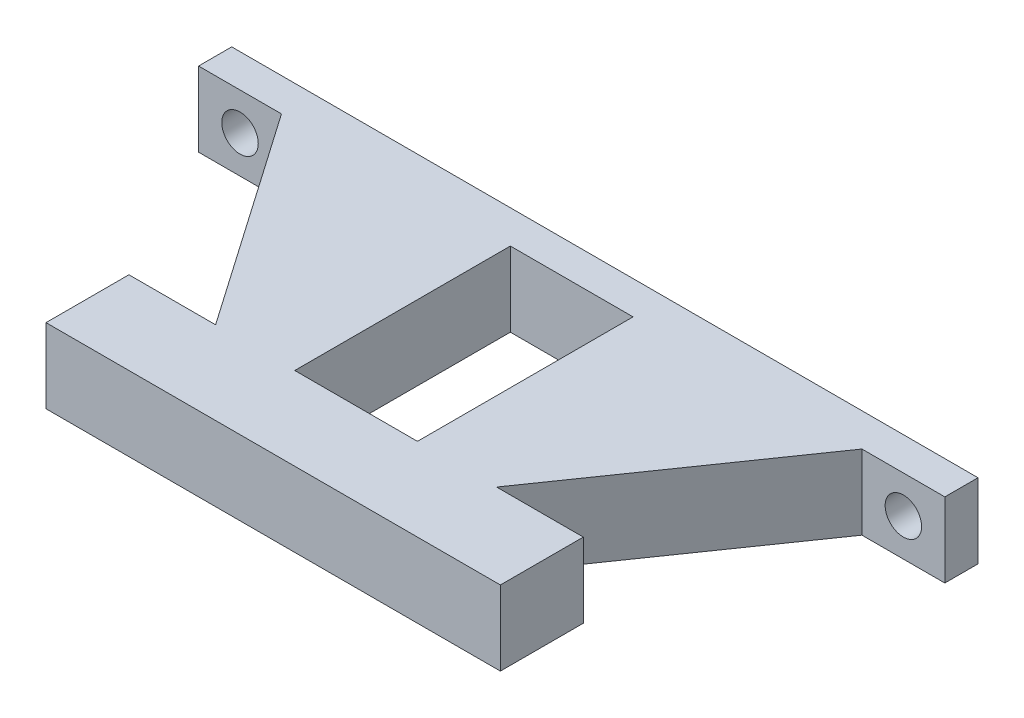
SolidWorks part; units mm, degrees
ref_plane "Front Plane" through (0, 0, 0) normal (0, 0, 1) x (1, 0, 0)
ref_plane "Top Plane" through (0, 0, 0) normal (0, 1, 0) x (1, 0, 0)
ref_plane "Right Plane" through (0, 0, 0) normal (1, 0, 0) x (0, 0, -1)
sketch "Sketch1" plane through (0, 0, 0) normal (0, 0, 1) x (1, 0, 0)
  line L3 (0, 2.54) -> (0, 16.409)
  line L4 (-57.15, 2.54) -> (-57.15, -2.54)
  line L6 (57.15, 2.54) -> (57.15, -2.54)
  line L9 (57.15, 2.54) -> (57.15, 5.715)
  line L10 (-57.15, 2.54) -> (-57.15, 5.715)
  line L11 (0, 0) -> (6.9271, 0)
  line L12 (57.15, -2.54) -> (57.15, -5.715)
  line L13 (-57.15, -2.54) -> (-57.15, -5.715)
  line L14 (-57.15, 5.715) -> (57.15, 5.715)
  line L15 (57.15, -5.715) -> (-57.15, -5.715)
  circle A0 centre (50.8, 0) radius 2.794
  circle A1 centre (-50.8, 0) radius 2.794
  point P4 (0, 0)
  dimension "D2" = 5.588
  dimension "D3" = 5.588
  dimension "D1" = 101.6
  dimension "D5" = 3.175
  dimension "D6" = 3.175
extrude "Boss-Extrude1" add sketch "Sketch1" along normal blind 5.08
sketch "Sketch2" plane through (0, 5.715, 0) normal (0, 1, 0) x (1, 0, 0)
  line L0 (-57.15, 0) -> (-57.15, -5.08)
  line L1 (-57.15, 0) -> (57.0574, 0)
  line L2 (-57.15, -5.08) -> (57.0574, -5.08)
  line L3 (57.0574, 0) -> (57.0574, -5.08)
sketch "Sketch3" plane through (0, 0, 5.08) normal (0, 0, 1) x (1, 0, 0)
  line L0 (-57.15, 5.715) -> (57.0574, 5.715) construction
  line L1 (-12.7, -5.715) -> (12.7, -5.715)
  line L2 (-12.7, -5.715) -> (-12.7, 5.715)
  line L3 (-12.7, 5.715) -> (12.7, 5.715)
  line L4 (12.7, -5.715) -> (12.7, 5.715)
  line L5 (-12.7, -5.715) -> (12.7, 5.715) construction
  line L6 (-12.7, 5.715) -> (12.7, -5.715) construction
  point P0 (0, 0)
  dimension "D1" = 25.4
extrude "Boss-Extrude2" add sketch "Sketch3" along normal blind 45.72
sketch "Sketch4" plane through (0, 0, 50.8) normal (0, 0, 1) x (1, 0, 0)
  line L0 (0, 0) -> (0, 10.3542)
  line L1 (-12.7, -5.715) -> (12.7, -5.715) construction
  line L2 (12.7, 5.715) -> (34.7967, 5.715)
  line L3 (12.7, 5.715) -> (12.7, -5.715)
  line L4 (12.7, -5.715) -> (34.7967, -5.715)
  line L5 (34.7967, 5.715) -> (34.7967, -5.715)
  line L6 (-12.7, -5.715) -> (-34.7967, -5.715)
  line L7 (-34.7967, 5.715) -> (-34.7967, -5.715)
  line L8 (-12.7, 5.715) -> (-34.7967, 5.715)
  line L9 (-12.7, 5.715) -> (-12.7, -5.715)
  line M6 (12.7, -5.715) -> (12.7, 5.715)
  line M8 (-12.7, 5.715) -> (-12.7, -5.715)
  dimension "D1" = 0
extrude "Boss-Extrude3" add sketch "Sketch4" against normal blind 12.7 contours L5 L2 L4 M6 | L8 L7 L6 M8
sketch "Sketch5" plane through (0, -5.715, 0) normal (0, -1, 0) x (1, 0, 0)
  line L0 (0, 0) -> (0, -16.8877)
  line L2 (-57.15, 5.08) -> (57.0574, 5.08) construction
  line L4 (-12.7, 5.08) -> (-44.45, 5.08)
  line L7 (12.7, 5.08) -> (44.45, 5.08)
  line L9 (-12.7, 5.08) -> (12.7, 5.08)
  line L10 (-12.7, 38.1) -> (-12.7, 50.8)
  line L11 (-34.7967, 50.8) -> (34.7967, 50.8) construction
  line L12 (-12.7, 50.8) -> (-44.45, 5.08)
  line L13 (12.7, 38.1) -> (12.7, 50.8)
  line L14 (12.7, 50.8) -> (44.45, 5.08)
  line L15 (-12.7, 50.8) -> (12.7, 50.8)
  line M3 (57.15, 5.08) -> (12.7, 5.08)
  line M4 (12.7, 5.08) -> (12.7, 38.1)
  line M5 (12.7, 38.1) -> (34.7967, 38.1)
  line M9 (-34.7967, 38.1) -> (-12.7, 38.1)
  line M10 (-12.7, 38.1) -> (-12.7, 5.08)
  line M11 (-12.7, 5.08) -> (-57.15, 5.08)
  dimension "D1" = 12.7
extrude "Boss-Extrude5" add sketch "Sketch5" against normal blind 11.43 contours L12 M9 M11 M10 | L14 M5 M4 M3
sketch "Sketch7" plane through (0, -5.715, 0) normal (0, -1, 0) x (1, 0, 0)
  line L0 (-34.7967, 38.1) -> (-9.3967, 38.1)
  line L1 (34.7967, 38.1) -> (9.3967, 38.1)
  line L2 (-9.3967, 38.1) -> (9.3967, 38.1)
  line L3 (-9.3967, 38.1) -> (-9.3967, 5.08)
  line L4 (9.3967, 38.1) -> (9.3967, 5.08)
  line L5 (-9.3967, 5.08) -> (9.3967, 5.08)
  line L6 (-57.15, 5.08) -> (57.0574, 5.08) construction
  dimension "D1" = 25.4
  dimension "D2" = 25.4
  dimension "D3" = 0
extrude "Cut-Extrude3" cut sketch "Sketch7" against normal blind 12.7 contours L3 L5 L4 L2
